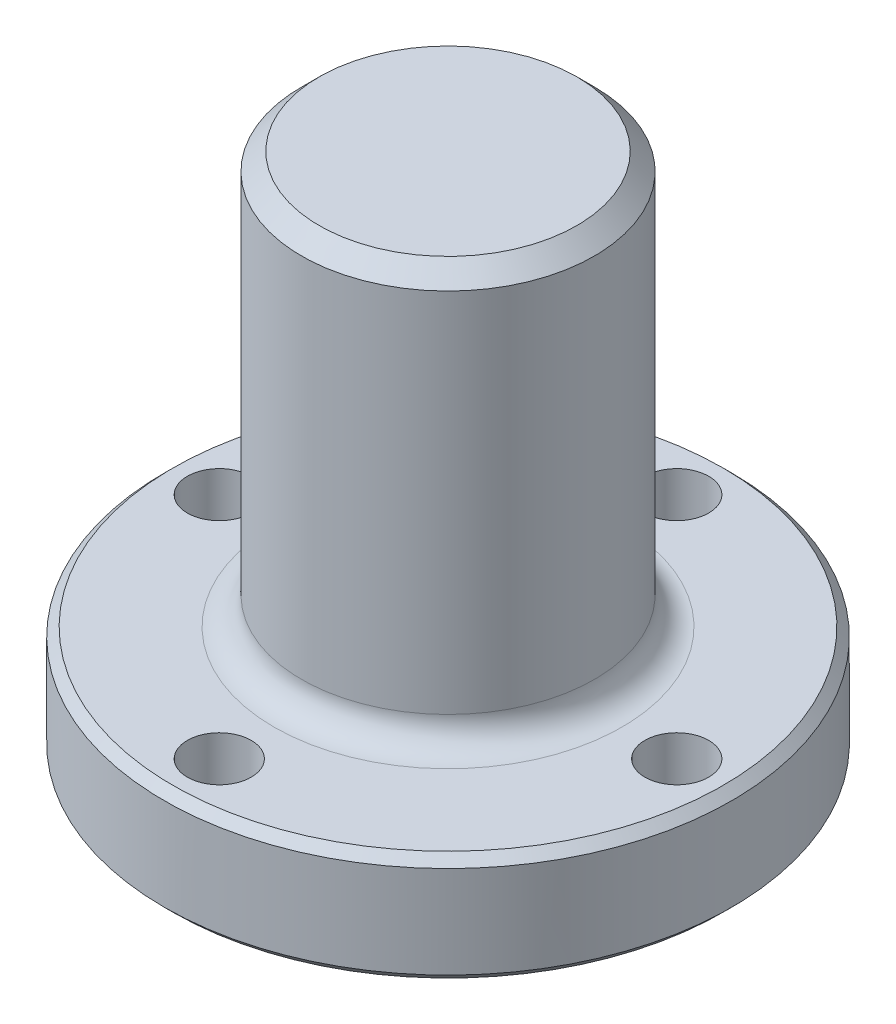
SolidWorks part; units mm, degrees
ref_plane "Front Plane" through (0, 0, 0) normal (1, 0, 0) x (0, 1, 0)
ref_plane "Top Plane" through (0, 0, 0) normal (0, 0, 1) x (0, 1, 0)
ref_plane "Right Plane" through (0, 0, 0) normal (0, 1, 0) x (-1, 0, 0)
sketch "Sketch1" plane through (0, 0, 0) normal (0, 0, 1) x (0, 1, 0)
  line L0 (-25.0317, 0) -> (-25.0317, 8.7122)
  line L1 (-25.0317, 8.7122) -> (-20.2057, 8.7122)
  line L2 (-20.2057, 8.7122) -> (-20.2057, 24.6126)
  line L3 (-20.2057, 24.6126) -> (-10.6807, 24.6126)
  line L4 (-10.6807, 24.6126) -> (-10.6807, 12.7)
  line L5 (-10.6807, 12.7) -> (25.0317, 12.7)
  line L6 (25.0317, 12.7) -> (25.0317, 0)
  line L7 (25.0317, 0) -> (-25.0317, 0)
  line L8 (-50.4317, 0) -> (50.4317, 0) construction
  point P10 (0, 0)
  dimension "D1" = 35.7124
  dimension "D2" = 45.2374
  dimension "D3" = 50.0634
  dimension "D4" = 11.9126
  dimension "D5" = 15.9004
  dimension "D6" = 24.6126
revolve "Revolve1" add sketch "Sketch1" angle 360 about L8
fillet "Fillet1" radius 2.3876 1 edges at (0, -10.6807, -12.7)
chamfer "Chamfer1" distance 0.762 angle 45 3 edges at (0, -10.6807, -24.6126) (0, -20.2057, -24.6126) (0, -25.0317, -8.7122)
chamfer "Chamfer2" distance 1.524 angle 45 1 edges at (0, 25.0317, -12.7)
sketch "Sketch2" plane through (0, 0, 0) normal (0, 1, 0) x (-1, 0, 0)
  circle A0 centre (19.8374, 0) radius 2.7686
  circle A1 centre (0, 19.8374) radius 2.7686
  circle A2 centre (-19.8374, 0) radius 2.7686
  circle A3 centre (0, -19.8374) radius 2.7686
  point P8 (0, 0)
  dimension "D1" = 5.5372
  dimension "D2" = 5.5372
  dimension "D3" = 5.5372
  dimension "D4" = 5.5372
  dimension "D5" = 19.8374
  dimension "D6" = 39.6748
  dimension "D7" = 19.8374
  dimension "D8" = 39.6748
extrude "Cut-Extrude2" cut sketch "Sketch2" against normal blind 10.6807 from offset 10.6807
